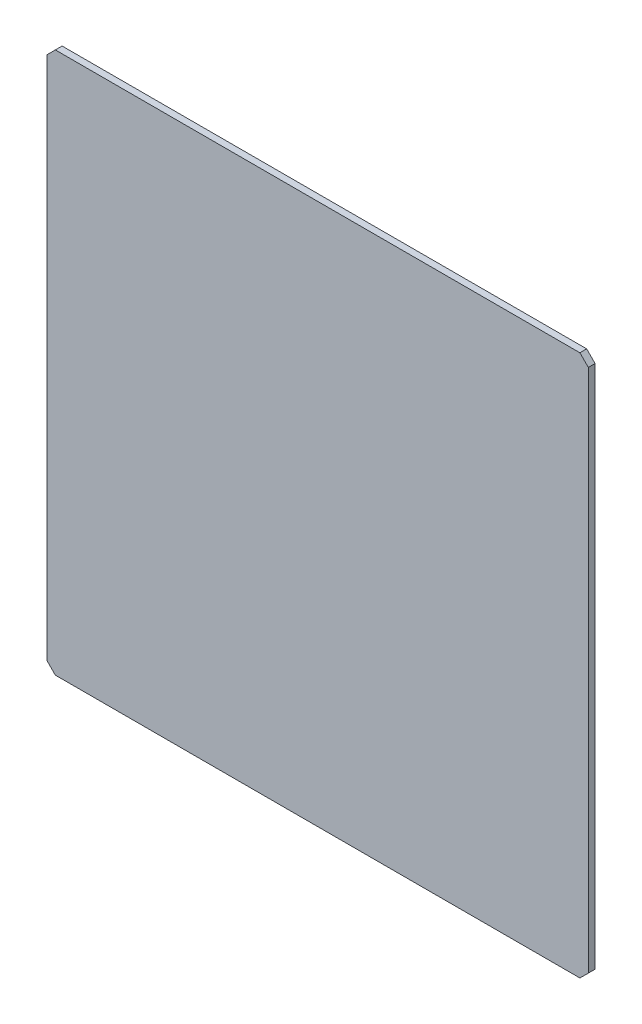
SolidWorks part; units mm, degrees
ref_plane "Front Plane" through (0, 0, 0) normal (0, 0, 1) x (1, 0, 0)
ref_plane "Top Plane" through (0, 0, 0) normal (0, 1, 0) x (1, 0, 0)
ref_plane "Right Plane" through (0, 0, 0) normal (1, 0, 0) x (0, 0, -1)
sketch "Sketch2" plane through (0, 0, 0) normal (0, 0, 1) x (1, 0, 0)
  line L1 (-160, -160) -> (160, -160)
  line L2 (-160, -160) -> (-160, 160)
  line L3 (-160, 160) -> (160, 160)
  line L4 (160, -160) -> (160, 160)
  line L5 (-160, -160) -> (160, 160) construction
  line L6 (-160, 160) -> (160, -160) construction
  point P0 (0, 0)
  dimension "D2" = 320
  dimension "D1" = 320
extrude "Boss-Extrude1" add sketch "Sketch2" along normal blind 4
chamfer "Chamfer1" distance 5 angle 45 4 edges at (160, -160, 2) (160, 160, 2) (-160, -160, 2) (-160, 160, 2)
equation "\"glass_x\"= \"heater_pad_x@print_bed.Assembly\""
equation "\"glass_y\"= \"heater_pad_y@print_bed.Assembly\""
equation "\"glass_z\"= 4"
equation "\"D2@Sketch2\" = \"glass_y\""
equation "\"D1@Sketch2\"= \"glass_x\""
equation "\"D1@Boss-Extrude1\"=\"glass_z\""
